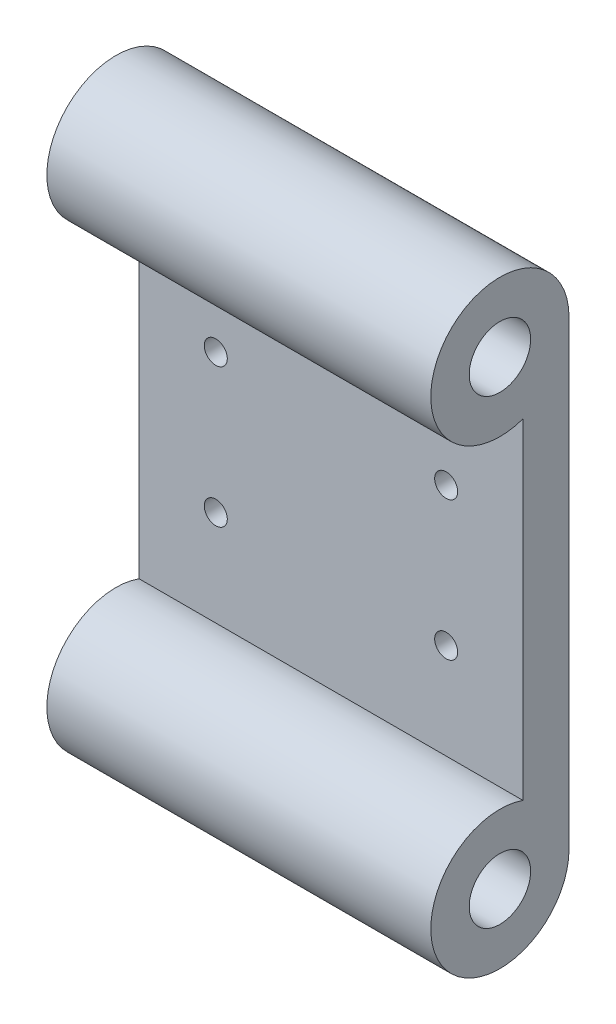
SolidWorks part; units mm, degrees
material "ABS"
ref_plane "Plano frontal" through (0, 0, 0) normal (0, 0, 1) x (1, 0, 0)
ref_plane "Plano superior" through (0, 0, 0) normal (0, 1, 0) x (1, 0, 0)
ref_plane "Plano direito" through (0, 0, 0) normal (1, 0, 0) x (0, 0, -1)
sketch "Esboço2" plane through (0, 0, 0) normal (1, 0, 0) x (0, 0, -1)
  line L0 (0, 30) -> (0, -30) construction
  line L1 (9, 30) -> (9, -30)
  line L2 (3, -21.5147) -> (3, 21.5147)
  circle A0 centre (0, 30) radius 4
  arc A1 (9, 30) -> (3, 21.5147) centre (0, 30) ccw
  arc A2 (3, -21.5147) -> (9, -30) centre (0, -30) ccw
  circle A3 centre (0, -30) radius 4
  circle A4 centre (0, 30) radius 4 construction
  circle A5 centre (0, -30) radius 4 construction
  point P8 (0, 0)
  dimension "D1" = 8
  dimension "D2" = 8
  dimension "D3" = 18
  dimension "D4" = 60
  dimension "D5" = 6
extrude "Ressalto-extrusão1" add sketch "Esboço2" along normal blind 50
sketch "Esboço5" plane through (0, 0, -3) normal (0, 0, 1) x (1, 0, 0)
  line L0 (50, 0) -> (0, 0) construction
  line L1 (50, 21.5147) -> (50, -21.5147) construction
  line L9 (10, -9.0444) -> (10, 9.0444) construction
  line L10 (0, 21.5147) -> (0, -21.5147) construction
  line L12 (40, -9.0444) -> (40, 9.0444) construction
  circle A5 centre (10, 9.0444) radius 1.5
  circle A6 centre (40, 9.0444) radius 1.5
  circle A7 centre (40, -9.0444) radius 1.5
  circle A8 centre (10, -9.0444) radius 1.5
  point P18 (25, 0)
  point P20 (10, 0)
  point P25 (40, 0)
  point P28 (25, 0)
  point P30 (30, 0)
  dimension "D5" = 3
  dimension "D7" = 10
  dimension "D8" = 30
extrude "Corte-extrusão2" cut sketch "Esboço5" against normal blind 40
